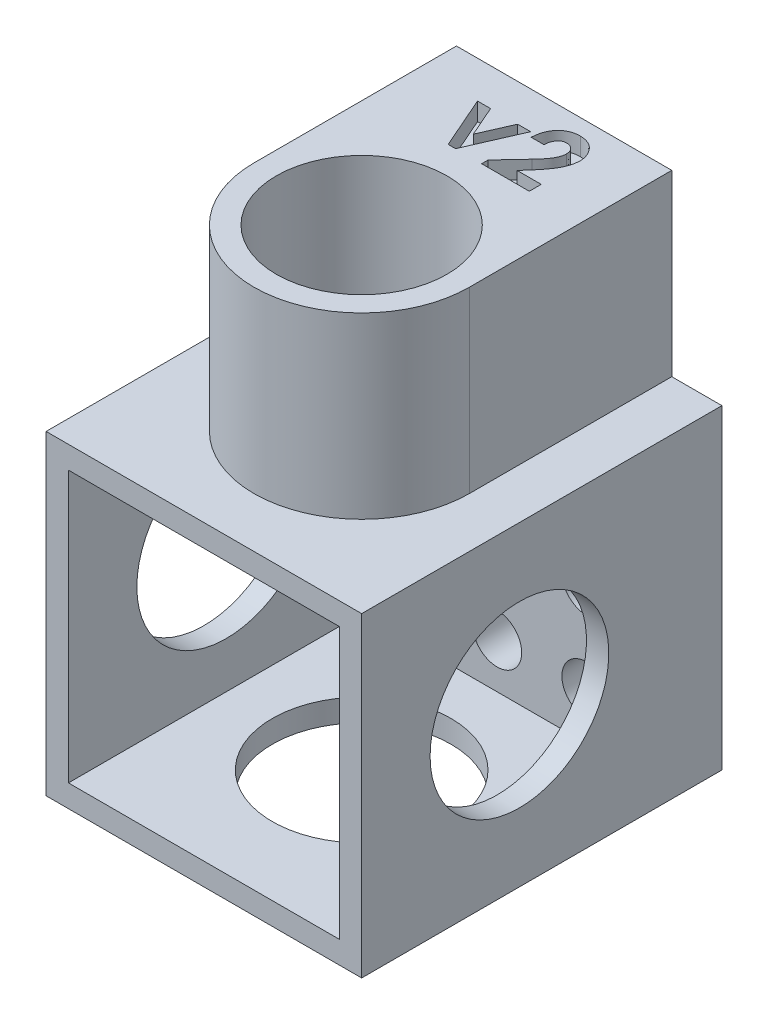
SolidWorks part; units mm, degrees
ref_plane "Front Plane" through (0, 0, 0) normal (0, 0, 1) x (1, 0, 0)
ref_plane "Top Plane" through (0, 0, 0) normal (0, 1, 0) x (1, 0, 0)
ref_plane "Right Plane" through (0, 0, 0) normal (1, 0, 0) x (0, 0, -1)
sketch "Sketch1" plane through (0, 0, 0) normal (0, 1, 0) x (1, 0, 0)
  line L1 (-19.25, -19.25) -> (19.25, -19.25)
  line L2 (-19.25, -19.25) -> (-19.25, 19.25)
  line L3 (-19.25, 19.25) -> (19.25, 19.25)
  line L4 (19.25, -19.25) -> (19.25, 19.25)
  line L5 (-19.25, -19.25) -> (19.25, 19.25) construction
  line L6 (-19.25, 19.25) -> (19.25, -19.25) construction
  line L7 (-22.425, -22.425) -> (22.425, -22.425)
  line L8 (-22.425, -22.425) -> (-22.425, 22.425)
  line L9 (-22.425, 22.425) -> (22.425, 22.425)
  line L10 (22.425, -22.425) -> (22.425, 22.425)
  line L11 (-22.425, -22.425) -> (22.425, 22.425) construction
  line L12 (-22.425, 22.425) -> (22.425, -22.425) construction
  point P0 (0, 0)
  point P6 (0, 0)
  dimension "D1" = 38.5
  dimension "D2" = 38.5
  dimension "D3" = 3.175
  dimension "D4" = 3.175
extrude "Boss-Extrude1" add sketch "Sketch1" along normal mid plane 38.5
sketch "Sketch2" plane through (0, 19.25, 0) normal (0, 1, 0) x (1, 0, 0)
  line L1 (-22.425, 22.425) -> (22.425, 22.425)
  line L2 (-22.425, 22.425) -> (-22.425, -22.425)
  line L3 (-22.425, -22.425) -> (22.425, -22.425)
  line L4 (22.425, 22.425) -> (22.425, -22.425)
extrude "Boss-Extrude2" add sketch "Sketch2" along normal blind 3.175
sketch "Sketch3" plane through (0, -19.25, 0) normal (0, -1, 0) x (1, 0, 0)
  line L1 (22.425, -22.425) -> (-22.425, -22.425)
  line L2 (22.425, -22.425) -> (22.425, 22.425)
  line L3 (22.425, 22.425) -> (-22.425, 22.425)
  line L4 (-22.425, -22.425) -> (-22.425, 22.425)
extrude "Boss-Extrude3" add sketch "Sketch3" along normal blind 3.175
sketch "Sketch5" plane through (0, -22.425, -22.425) normal (0, 1, 0) x (1, 0, 0)
  circle A0 centre (0, -22.425) radius 12.7
  dimension "D1" = 25.4
extrude "Cut-Extrude1" cut sketch "Sketch5" along normal up to next (3.175 mm away) from surface at 0 starting at face at (0, -22.425, 0)
sketch "Sketch6" plane through (0, 0, 0) normal (0, 1, 0) x (1, 0, 0)
  circle A0 centre (0, 0) radius 10
  dimension "D1" = 20
extrude "Cut-Extrude2" cut sketch "Sketch6" against normal up to next (19.25 mm away) from surface at 22.425 starting at face at (0, 22.425, 0)
sketch "Sketch7" plane through (-22.425, 0, 0) normal (-1, 0, 0) x (0, 0, 1)
  circle A0 centre (0, 0) radius 12.7
  dimension "D1" = 25.4
extrude "Cut-Extrude3" cut sketch "Sketch7" against normal through all from surface at 0 starting at face at (-22.425, 0, 0)
sketch "Sketch8" plane through (0, 0, -22.425) normal (0, 0, -1) x (-1, 0, 0)
  line L0 (-12.7, 12.7) -> (0, 12.7) construction
  line L1 (-22.425, -22.425) -> (22.425, -22.425)
  line L2 (-22.425, 22.425) -> (-22.425, -22.425)
  line L3 (-22.425, 22.425) -> (22.425, 22.425)
  line L4 (22.425, -22.425) -> (22.425, 22.425)
  circle A0 centre (-12.7, 12.7) radius 2.2225
  circle A1 centre (0, 12.7) radius 2.2225
  circle A2 centre (12.7, 12.7) radius 2.2225
  circle A3 centre (0, 0) radius 2.2225
  circle A4 centre (12.7, 0) radius 2.2225
  circle A5 centre (0, -12.7) radius 2.2225
  circle A6 centre (12.7, -12.7) radius 2.2225
  circle A7 centre (-12.7, 0) radius 2.2225
  circle A8 centre (-12.7, -12.7) radius 2.2225
  dimension "D1" = 4.445
  dimension "D2" = 12.7
  dimension "D3" = 12.7
  dimension "D6" = 12.7
  dimension "D4" = 3
  dimension "D5" = 3
extrude "Boss-Extrude4" add sketch "Sketch8" along normal blind 6.35
sketch "Sketch9" plane through (0, 0, -19.25) normal (0, 0, 1) x (1, 0, 0)
  line L0 (12.7, 12.7) -> (0, 12.7) construction
  circle A0 centre (12.7, 12.7) radius 3.4925
  circle A1 centre (0, 12.7) radius 3.4925
  circle A2 centre (-12.7, 12.7) radius 3.4925
  circle A3 centre (0, 0) radius 3.4925
  circle A4 centre (-12.7, 0) radius 3.4925
  circle A5 centre (0, -12.7) radius 3.4925
  circle A6 centre (-12.7, -12.7) radius 3.4925
  circle A7 centre (12.7, 0) radius 3.4925
  circle A8 centre (12.7, -12.7) radius 3.4925
  dimension "D1" = 6.985
  dimension "D4" = 12.7
  dimension "D2" = 3
  dimension "D3" = 3
extrude "Cut-Extrude4" cut sketch "Sketch9" against normal blind 6.35
sketch "Sketch10" plane through (0, 0, 22.425) normal (0, 0, 1) x (1, 0, 0)
  line L0 (-22.425, 22.425) -> (-22.425, -22.425) construction
  line L1 (-19.25, -19.25) -> (19.25, -19.25)
  line L2 (-19.25, -19.25) -> (-19.25, 19.25)
  line L3 (-19.25, 19.25) -> (19.25, 19.25)
  line L4 (19.25, -19.25) -> (19.25, 19.25)
  line L5 (-19.25, -19.25) -> (19.25, 19.25) construction
  line L6 (-19.25, 19.25) -> (19.25, -19.25) construction
  line L7 (-22.425, 22.425) -> (22.425, 22.425) construction
  point P0 (0, 0)
  dimension "D1" = 3.175
  dimension "D2" = 3.175
extrude "Cut-Extrude5" cut sketch "Sketch10" against normal up to next
sketch "Sketch11" plane through (0, 22.425, 0) normal (0, 1, 0) x (1, 0, 0)
  line L2 (-15.3035, 0) -> (-15.3035, 28.775)
  line L3 (-15.3035, 28.775) -> (15.3035, 28.775)
  line L4 (15.3035, 0) -> (15.3035, 28.775)
  line L5 (-22.425, 28.775) -> (22.425, 28.775) construction
  circle A0 centre (0, 0) radius 12.1285
  arc A1 (-15.3035, 0) -> (15.3035, 0) centre (0, 0) ccw
  point P7 (15.7163, 0)
  point P8 (15.7163, 0)
  point P9 (0, 0)
  point P10 (-15.7163, 22.6131)
  point P11 (0, -12.1285)
  point P12 (0, -15.3035)
  point P13 (-15.3035, 0)
  point P14 (15.3035, 0)
  point P17 (22.425, 6.3279)
  dimension "D1" = 24.257
  dimension "D2" = 3.175
extrude "Boss-Extrude5" add sketch "Sketch11" along normal blind 25.4
sketch "Sketch12" plane through (0, 0, 0) normal (0, 1, 0) x (1, 0, 0)
  line L0 (-13.7875, 16.075) -> (15.0923, 16.075) construction
  line L1 (15.3035, 28.775) -> (-15.3035, 28.775) construction
  text T0 "<b>v2</b>" font "Century Gothic" height 10.16
  dimension "D1" = 12.7
extrude "Cut-Extrude6" cut sketch "Sketch12" against normal blind 2.54 from surface at 47.825 starting at face at (0, 47.825, -10.5616)
